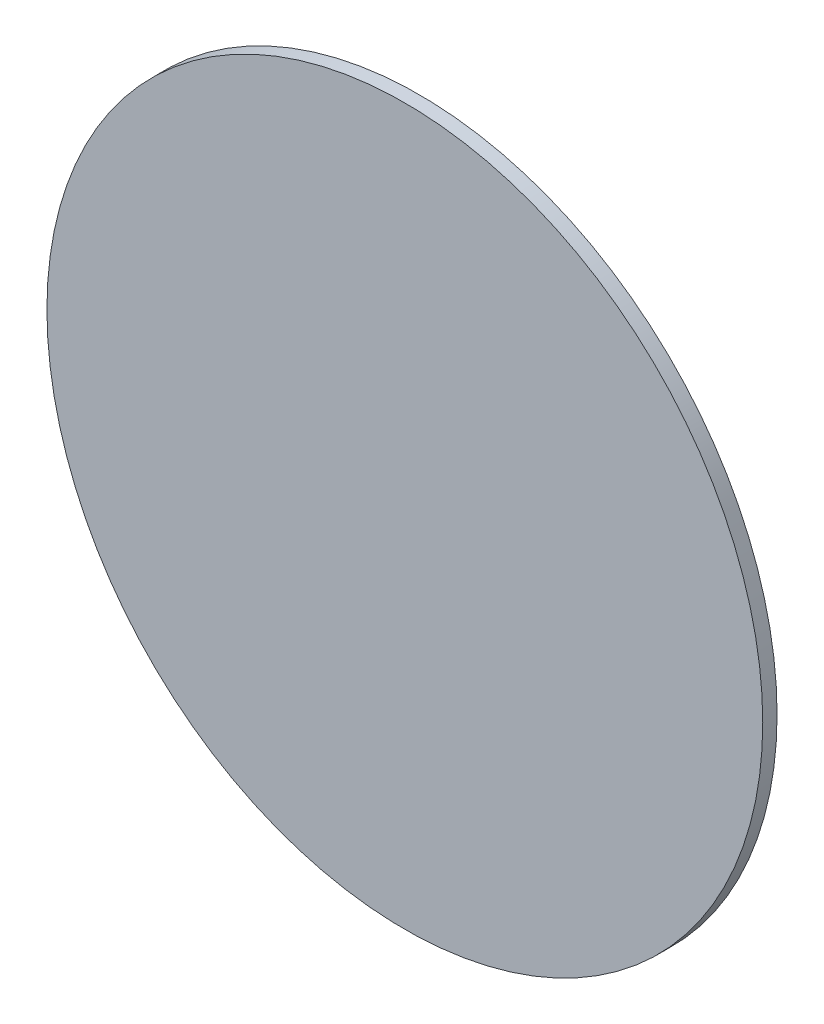
SolidWorks part; units mm, degrees
ref_plane "Front Plane" through (0, 0, 0) normal (0, 0, 1) x (1, 0, 0)
ref_plane "Top Plane" through (0, 0, 0) normal (0, 1, 0) x (1, 0, 0)
ref_plane "Right Plane" through (0, 0, 0) normal (1, 0, 0) x (0, 0, -1)
sketch "Sketch1" plane through (0, 0, 0) normal (0, 0, 1) x (1, 0, 0)
  circle A0 centre (0, 0) radius 125
  dimension "D1" = 250
extrude "Boss-Extrude1" add sketch "Sketch1" along normal blind 5
